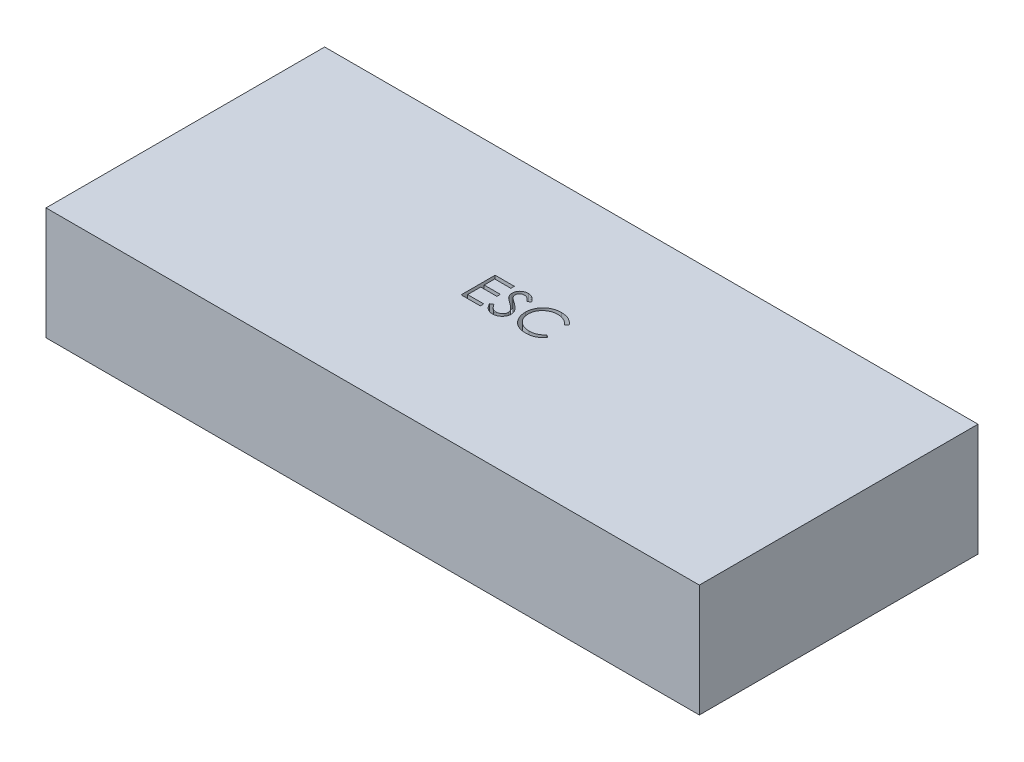
SolidWorks part; units mm, degrees
ref_plane "Front Plane" through (0, 0, 0) normal (0, 0, 1) x (1, 0, 0)
ref_plane "Top Plane" through (0, 0, 0) normal (0, 1, 0) x (1, 0, 0)
ref_plane "Right Plane" through (0, 0, 0) normal (1, 0, 0) x (0, 0, -1)
sketch "Sketch1" plane through (0, 0, 0) normal (0, 1, 0) x (1, 0, 0)
  line L1 (-30.48, -13) -> (30.48, -13)
  line L2 (-30.48, -13) -> (-30.48, 13)
  line L3 (-30.48, 13) -> (30.48, 13)
  line L4 (30.48, -13) -> (30.48, 13)
  line L5 (-30.48, -13) -> (30.48, 13) construction
  line L6 (-30.48, 13) -> (30.48, -13) construction
  point P0 (0, 0)
  dimension "D1" = 60.96
  dimension "D2" = 25.9999
extrude "Boss-Extrude1" add sketch "Sketch1" along normal blind 10.5
sketch "Sketch2" plane through (0, 10.5, 0) normal (0, 1, 0) x (1, 0, 0)
  text T0 "ESC"
extrude "Cut-Extrude1" cut sketch "Sketch2" against normal blind 1.27
equation "\"D1@Sketch1\"=\"ESC Y@Quad Assemb.sldasm\""
equation "\"D2@Sketch1\"=\"ESC X@Quad Assemb.sldasm\""
equation "\"D1@Boss-Extrude1\"=\"ESC Z@Quad Assemb.sldasm\""
